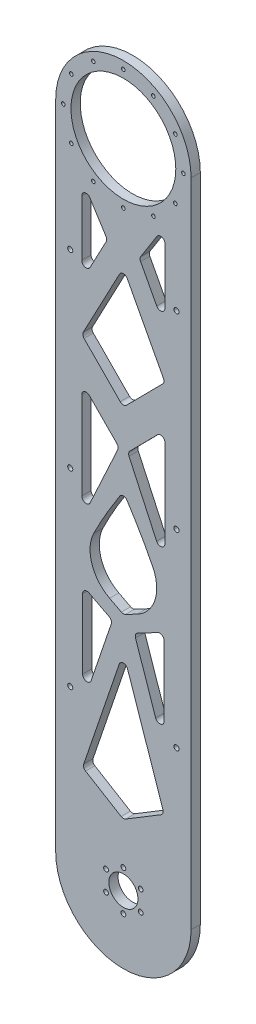
SolidWorks part; units mm, degrees
material "1060 Alloy"
ref_plane "Front Plane" through (0, 0, 0) normal (0, 0, 1) x (1, 0, 0)
ref_plane "Top Plane" through (0, 0, 0) normal (0, 1, 0) x (1, 0, 0)
ref_plane "Right Plane" through (0, 0, 0) normal (1, 0, 0) x (0, 0, -1)
sketch "Sketch2" plane through (0, 0, 0) normal (0, 0, 1) x (1, 0, 0)
  line L0 (0, 0) -> (0, 500) construction
  line L1 (-46.5, 0) -> (-46.5, 500)
  line L2 (46.5, 0) -> (46.5, 500)
  arc A0 (-46.5, 0) -> (46.5, 0) centre (0, 0) ccw
  arc A1 (46.5, 500) -> (-46.5, 500) centre (0, 500) ccw
  circle A2 centre (0, 500) radius 37.25 construction
  circle A3 centre (0, 0) radius 10
  circle A4 centre (0, 13.75) radius 1.65
  circle A5 centre (0, 0) radius 13.75 construction
  circle A6 centre (11.9078, 6.875) radius 1.65
  circle A7 centre (11.9078, -6.875) radius 1.65
  circle A8 centre (0, -13.75) radius 1.65
  circle A9 centre (-11.9078, -6.875) radius 1.65
  circle A10 centre (-11.9078, 6.875) radius 1.65
  point P3 (0, 250)
  point P27 (0, 0)
  dimension "D2" = 74.5
  dimension "D4" = 20
  dimension "D5" = 3.3
  dimension "D6" = 27.5
  dimension "D3" = 46.5
  dimension "D1" = 500
  dimension "D7" = 6
extrude "Boss-Extrude1" add sketch "Sketch2" along normal blind 6.35
sketch "Sketch4" plane through (0, 0, 6.35) normal (0, 0, 1) x (1, 0, 0)
  line L0 (0, 500) -> (0, 999.1647) construction
  line L29 (46.5, 500) -> (-46.5, 500) construction
  line L31 (28.0053, 59.376) -> (0, 42.4117)
  line L32 (0, 141.6934) -> (28.0053, 59.376)
  line L33 (-28.0053, 59.376) -> (0, 141.6934)
  line L34 (0, 42.4117) -> (-28.0053, 59.376)
  line L35 (-7.5, 156.9059) -> (-28.0053, 96.6336)
  line L36 (-28.0053, 167.5829) -> (-7.5, 156.9059)
  line L37 (-28.0053, 96.6336) -> (-28.0053, 167.5829)
  line L38 (28.0053, 167.5829) -> (7.5, 156.9059)
  line L39 (28.0053, 96.6336) -> (28.0053, 167.5829)
  line L40 (7.5, 156.9059) -> (28.0053, 96.6336)
  line L41 (0, 164.2751) -> (28.5505, 179.1412)
  line L42 (0, 164.2751) -> (-28.5505, 179.1412)
  line L43 (28.5505, 259.5868) -> (3, 314.9383)
  line L44 (28.5505, 340.7931) -> (28.5505, 259.5868)
  line L45 (3, 314.9383) -> (28.5505, 340.7931)
  line L46 (-3, 314.9383) -> (-28.5505, 340.7931)
  line L47 (-28.5505, 259.5868) -> (-3, 314.9383)
  line L48 (-28.5505, 340.7931) -> (-28.5505, 259.5868)
  line L49 (0, 423.1428) -> (-28.5505, 369.2462)
  line L50 (-28.5505, 369.2462) -> (0, 340.3557)
  line L51 (0, 340.3557) -> (28.5505, 369.2462)
  line L52 (0, 423.1428) -> (28.5505, 369.2462)
  line L53 (-28.5505, 462.0952) -> (-28.5505, 401.2902)
  line L54 (-11, 434.4215) -> (-28.5505, 462.0952)
  line L55 (-28.5505, 401.2902) -> (-11, 434.4215)
  line L56 (28.5505, 401.2902) -> (11, 434.4215)
  line L57 (28.5505, 462.0952) -> (28.5505, 401.2902)
  line L58 (11, 434.4215) -> (28.5505, 462.0952)
  arc A0 (46.5, 500) -> (-46.5, 500) centre (0, 500) ccw construction
  arc A1 (46.5, 500) -> (-46.5, 500) centre (0, 500) ccw construction
  spline S2 degree 3 poles (28.5505, 179.1412) (45.3203, 216.9857) (19.4301, 259.7903) (0, 290.0258) knots 0 0 0 0 1 1 1 1
  spline S3 degree 3 poles (-28.5505, 179.1412) (-45.3203, 216.9857) (-19.4301, 259.7903) (0, 290.0258) knots 0 0 0 0 1 1 1 1
extrude "Cut-Extrude1" cut sketch "Sketch4" against normal blind 10
fillet "Fillet3" radius 3 30 edges at (-11, 434.4215, 3.175) (-28.5505, 401.2902, 3.175) (28.5505, 401.2902, 3.175) (11, 434.4215, 3.175) (28.5505, 462.0952, 3.175) (-28.5505, 462.0952, 3.175) (0, 423.1428, 3.175) (-28.5505, 369.2462, 3.175) (28.5505, 369.2462, 3.175) (0, 340.3557, 3.175) (28.5505, 340.7931, 3.175) (-28.5505, 340.7931, 3.175) (-3, 314.9383, 3.175) (3, 314.9383, 3.175) (28.5505, 259.5868, 3.175) (-28.5505, 259.5868, 3.175) (28.5505, 179.1412, 3.175) (0, 290.0258, 3.175) (-28.5505, 179.1412, 3.175) (0, 164.2751, 3.175) (-28.0053, 96.6336, 3.175) (28.0053, 96.6336, 3.175) (7.5, 156.9059, 3.175) (-28.0053, 167.5829, 3.175) (28.0053, 167.5829, 3.175) (0, 141.6934, 3.175) (28.0053, 59.376, 3.175) (-28.0053, 59.376, 3.175) (0, 42.4117, 3.175) (-7.5, 156.9059, 3.175)
sketch "Sketch5" plane through (0, 0, 6.35) normal (0, 0, 1) x (1, 0, 0)
  line L0 (0, -46.5) -> (108.8395, -46.5) construction
  line L1 (46.5, 100) -> (-46.5, 100) construction
  line L2 (46.5, 0) -> (46.5, 500) construction
  line L3 (-46.5, 500) -> (-46.5, 0) construction
  line L4 (-46.5, 106.35) -> (46.5, 106.35) construction
  line L5 (36.5, 106.35) -> (36.5, 100) construction
  line L6 (0, 106.35) -> (0, 100) construction
  line L7 (-46.5, 256.35) -> (46.5, 256.35) construction
  line L8 (-46.5, 181.35) -> (46.5, 181.35) construction
  line L9 (-46.5, 337.7) -> (46.5, 337.7) construction
  arc A1 (-46.5, 0) -> (46.5, 0) centre (0, 0) ccw construction
  circle A2 centre (36.5, 103.175) radius 1.75
  circle A3 centre (-36.5, 103.175) radius 1.75
  circle A4 centre (36.5, 259.525) radius 1.75
  circle A5 centre (-36.5, 259.525) radius 1.75
  circle A6 centre (36.5, 415.875) radius 1.75
  circle A7 centre (-36.5, 415.875) radius 1.75
  point P18 (36.5, 103.175)
  dimension "D2" = 3.5
  dimension "D1" = 146.5
  dimension "D3" = 10
  dimension "D4" = 6.35
  dimension "D5" = 150
  dimension "D6" = 81.35
  dimension "D7" = 81.35
extrude "Cut-Extrude2" cut sketch "Sketch5" against normal through all
sketch "Sketch6" plane through (0, 0, 6.35) normal (0, 0, 1) x (1, 0, 0)
  circle A0 centre (0, 500) radius 26.5
  arc A1 (46.5, 500) -> (-46.5, 500) centre (0, 500) ccw construction
  arc A2 (46.5, 500) -> (-46.5, 500) centre (0, 500) ccw construction
  dimension "D1" = 20
extrude "Cut-Extrude3" cut sketch "Sketch6" against normal blind 10
sketch "Sketch7" plane through (0, 0, 6.35) normal (0, 0, 1) x (1, 0, 0)
  line L1 (40.0163, 523.6842) -> (44.1104, 529.9682) construction
  line L2 (23.6842, 540.0163) -> (29.9682, 544.1104) construction
  line L3 (44.1104, 529.9682) -> (29.9682, 544.1104)
  line L4 (0, 500) -> (37.0393, 537.0393) construction
  line L5 (0, 500) -> (0, 546.5) construction
  arc A0 (46.5, 500) -> (-46.5, 500) centre (0, 500) ccw construction
  arc A1 (29.9682, 544.1104) -> (16.4747, 543.4837) centre (22.4977, 559.381) cw
  arc A2 (44.1104, 529.9682) -> (43.4837, 516.4747) centre (59.381, 522.4977) ccw
  arc A3 (16.4747, 543.4837) -> (43.4837, 516.4747) centre (0, 500) cw
  dimension "D3" = 17
  dimension "D5" = 17
  dimension "D1" = 20
  dimension "D2" = 7.5
  dimension "D4" = 8
  dimension "D6" = 8
  dimension "D7" = 45
extrude "Boss-Extrude2" add sketch "Sketch7" against normal up to surface (6.35 mm away) up to face at (26.5, 500, 0)
sketch "Sketch8" plane through (287.0393, 287.0393, 0) normal (0.7071, 0.7071, 0) x (0, 0, -1)
  line L0 (0, 363.5534) -> (-6.35, 363.5534) construction
  line L1 (0, 343.5534) -> (-6.35, 343.5534) construction
  line L2 (-6.35, 343.5534) -> (-6.35, 363.5534) construction
  point P0 (-3.175, 359.5534)
  point P1 (-3.175, 347.5534)
  dimension "D1" = 4
  dimension "D2" = 4
  dimension "D3" = 3.175
hole_wizard "Tap Drill for M3x0.5 Tap1" positions "Sketch8" profile "Sketch9" hole size "M3x0.5" standard "ANSI Metric"
sketch "Sketch9" plane through (32.7967, 541.282, 3.175) normal (0, 0, 1) x (-0.7071, 0.7071, 0)
  line L0 (0, 0) -> (0, 5.7511)
  line L1 (0, 5.7511) -> (1.25, 5)
  line L2 (1.25, 5) -> (1.25, 0)
  line L5 (1.25, 0) -> (0, 0)
  line L10 (0, 5.7511) -> (-1.25, 5) construction
  line L11 (0, -6.35) -> (0, 107.95) construction
  dimension "Hole Dia." = 2.5
  dimension "Hole Depth" = 5
  dimension "Drill Angle" = 118
pattern_circular "CirPattern2" count 2 every 90 about axis through (0, 500, 0) along (0, 0, 1) of "Boss-Extrude2", "Tap Drill for M3x0.5 Tap1"
sketch "Sketch10" plane through (0, 0, 6.35) normal (0, 0, 1) x (1, 0, 0)
  line L0 (-43.4837, 516.4747) -> (-63.4837, 516.4747)
  line L1 (43.4837, 516.4747) -> (63.4837, 516.4747)
  arc A0 (43.4837, 516.4747) -> (-43.4837, 516.4747) centre (0, 500) ccw
  arc A1 (46.5, 500) -> (43.4837, 516.4747) centre (0, 500) ccw construction
  arc A2 (-63.4837, 516.4747) -> (63.4837, 516.4747) centre (0, 500) cw
  dimension "D1" = 19.0866
  dimension "D2" = 20
extrude "Cut-Extrude4" cut sketch "Sketch10" against normal through all
sketch "Sketch11" plane through (0, 0, 6.35) normal (0, 0, 1) x (1, 0, 0)
  circle A0 centre (0, 500) radius 36
  circle A1 centre (0, 500) radius 26.5 construction
  dimension "D1" = 72
extrude "Cut-Extrude5" cut sketch "Sketch11" against normal through all
sketch "Sketch12" plane through (0, 0, 6.35) normal (0, 0, 1) x (1, 0, 0)
  line L0 (0, 536) -> (0, 546.5) construction
  circle A0 centre (0, 500) radius 41.25 construction
  circle A1 centre (0, 500) radius 36 construction
  arc A2 (46.5, 500) -> (-46.5, 500) centre (0, 500) ccw construction
  circle A3 centre (0, 541.25) radius 1.25
  circle A4 centre (20.625, 535.7235) radius 1.25
  circle A5 centre (35.7235, 520.625) radius 1.25
  circle A6 centre (41.25, 500) radius 1.25
  circle A7 centre (35.7235, 479.375) radius 1.25
  circle A8 centre (20.625, 464.2765) radius 1.25
  circle A9 centre (0, 458.75) radius 1.25
  circle A10 centre (-20.625, 464.2765) radius 1.25
  circle A11 centre (-35.7235, 479.375) radius 1.25
  circle A12 centre (-41.25, 500) radius 1.25
  circle A13 centre (-35.7235, 520.625) radius 1.25
  circle A14 centre (-20.625, 535.7235) radius 1.25
  point P9 (0, 541.25)
  point P36 (0, 500)
  dimension "D1" = 2.5
  dimension "D2" = 12
extrude "Cut-Extrude6" cut sketch "Sketch12" against normal through all both and the other way through all
sketch "Sketch13" plane through (0, 0, 0) normal (0, 0, -1) x (-1, 0, 0)
  line L0 (28.984, 180.1429) -> (28.984, 234.0954) construction
  line L1 (-28.984, 180.1429) -> (-28.984, 234.0954) construction
  line L2 (46.5, 234.0954) -> (-46.5, 234.0954)
  line L3 (46.5, 500) -> (46.5, 0) construction
  line L4 (-46.5, 0) -> (-46.5, 500) construction
  line L5 (46.5, 180.1429) -> (-46.5, 180.1429)
  line L6 (-46.5, 234.0954) -> (-46.5, 180.1429)
  line L7 (46.5, 234.0954) -> (46.5, 180.1429)
  spline S0 degree 3 poles (2.5314, 286.068) (21.3968, 256.4039) (44.1773, 216.1126) (28.984, 180.1429) knots 0.042883 0.042883 0.042883 0.042883 0.991187 0.991187 0.991187 0.991187 construction
  spline S1 degree 3 poles (-28.984, 180.1429) (-44.1773, 216.1126) (-21.3968, 256.4039) (-2.5314, 286.068) knots 0.008813 0.008813 0.008813 0.008813 0.957117 0.957117 0.957117 0.957117 construction
extrude "Cut-Extrude7" cut sketch "Sketch13" against normal through all
move or copy body "Body-Move/Copy1" bodies to move or copy 111 copy no translate (0, -52.7177, 0) parameters "D1"=0, "D2"=52.7177, "D3"=0
sketch "Sketch14" plane through (0, 180.1429, 0) normal (0, 1, 0) x (1, 0, 0)
  line L0 (-28.984, 0) -> (-46.5, 0) construction
  line L1 (-46.5, 0) -> (-46.5, -6.35) construction
  line L2 (-46.5, -6.35) -> (-28.984, -6.35) construction
  line L3 (-28.984, -6.35) -> (-28.984, 0) construction
  line L4 (28.984, -6.35) -> (46.5, -6.35) construction
  line L5 (46.5, -6.35) -> (46.5, 0) construction
  line L6 (46.5, 0) -> (28.984, 0) construction
  line L7 (28.984, 0) -> (28.984, -6.35) construction
  line L8 (-28.984, 0) -> (-46.5, 0)
  line L9 (-46.5, 0) -> (-46.5, -6.35)
  line L10 (-46.5, -6.35) -> (-28.984, -6.35)
  line L11 (-28.984, -6.35) -> (-28.984, 0)
  line L12 (28.984, -6.35) -> (46.5, -6.35)
  line L13 (46.5, -6.35) -> (46.5, 0)
  line L14 (46.5, 0) -> (28.984, 0)
  line L15 (28.984, 0) -> (28.984, -6.35)
extrude "Boss-Extrude3" add sketch "Sketch14" along normal up to surface (1.2348 mm away) up to face at (37.742, 181.3777, 3.175)
sketch "Sketch15" plane through (0, 0, 0) normal (0, 0, -1) x (-1, 0, 0)
  line L0 (-1.3855, 164.9966) -> (-27.606, 178.6494) construction
  line L1 (28.984, 181.3777) -> (28.984, 180.1429)
  line L2 (-28.984, 181.3777) -> (-28.984, 180.1429) construction
  line L3 (-9.4381, 169.1895) -> (-27.606, 178.6494)
  line L4 (-28.984, 181.3777) -> (-28.984, 180.1429)
  line L5 (0, 493.7823) -> (0, -46.5) construction
  line L6 (9.4381, 169.1895) -> (27.606, 178.6494)
  arc A0 (-20.3344, 202.3794) -> (-9.4381, 169.1895) centre (2.1078, 191.3636) ccw
  arc A1 (-28.984, 180.1429) -> (-27.606, 178.6494) centre (-26.2204, 181.3103) ccw construction
  arc A2 (-28.984, 180.1429) -> (-27.606, 178.6494) centre (-26.2204, 181.3103) ccw
  arc A3 (46.5, 447.2823) -> (-46.5, 447.2823) centre (0, 447.2823) ccw construction
  arc A4 (-46.5, 0) -> (46.5, 0) centre (0, 0) ccw construction
  arc A5 (28.984, 180.1429) -> (27.606, 178.6494) centre (26.2204, 181.3103) cw
  arc A6 (20.3344, 202.3794) -> (9.4381, 169.1895) centre (-2.1078, 191.3636) cw
  spline S0 degree 3 poles (1953.7087, 263.1445) (-2215.7642, -533.3919) (2154.4506, 1213.369) (-1849.5555, -532.5784) knots -2.670349 -2.670349 -2.670349 -2.670349 4.338748 4.338748 4.338748 4.338748 only from (-28.984, 181.3777) to (-2.5314, 233.3503) construction
  spline S1 degree 3 poles (28.984, 181.3777) (26.6659, 188.5284) (23.6788, 195.566) (20.3344, 202.3794) knots 0.47109 0.47109 0.47109 0.47109 0.656208 0.656208 0.656208 0.656208
  spline S2 degree 3 poles (-28.984, 181.3777) (-26.6659, 188.5284) (-23.6788, 195.566) (-20.3344, 202.3794) knots 0.47109 0.47109 0.47109 0.47109 0.656208 0.656208 0.656208 0.656208
  dimension "D1" = 25
  dimension "D2" = 540.2823
extrude "Boss-Extrude4" add sketch "Sketch15" against normal up to surface (6.35 mm away) up to face at (2.6453, 187.7844, 6.35)
sketch "Sketch16" plane through (0, 0, 0) normal (0, 0, -1) x (-1, 0, 0)
  line L0 (36.5, 103.175) -> (36.5, 363.1573) construction
  line L1 (-36.5, 103.175) -> (-36.5, 363.1573) construction
  circle A0 centre (-36.5, 363.1573) radius 1.75 construction
  circle A1 centre (36.5, 363.1573) radius 1.75 construction
  circle A2 centre (-36.5, 103.175) radius 1.75 construction
  circle A3 centre (36.5, 103.175) radius 1.75 construction
  circle A4 centre (-36.5, 363.1573) radius 1.75 construction
  circle A5 centre (36.5, 363.1573) radius 1.75 construction
  circle A6 centre (-36.5, 103.175) radius 1.75 construction
  circle A7 centre (36.5, 103.175) radius 1.75 construction
  circle A8 centre (36.5, 233.1662) radius 1.75
  circle A9 centre (-36.5, 233.1662) radius 1.75
  point P16 (36.5, 233.1662)
  point P18 (36.5, 233.1662)
extrude "Cut-Extrude8" cut sketch "Sketch16" against normal through all
sketch "Sketch17" plane through (0, 0, 0) normal (0, 0, -1) x (-1, 0, 0)
  circle A0 centre (36.5, 206.8073) radius 1.75 construction
  circle A1 centre (-36.5, 206.8073) radius 1.75 construction
  circle A2 centre (36.5, 206.8073) radius 1.75
  circle A3 centre (-36.5, 206.8073) radius 1.75
extrude "Boss-Extrude5" add sketch "Sketch17" against normal up to surface (6.35 mm away) up to face at (-34.75, 233.1662, 6.35)
equation "\"L1L\"=500"
equation "\"L1Thick\"=6.35"
equation "\"D1@Sketch2\"=\"L1L\""
equation "\"Harm-Drive-Outer\"=74.5"
equation "\"D2@Sketch2\"=\"Harm-Drive-Outer\""
equation "\"D1@Boss-Extrude1\"=\"L1Thick\""
